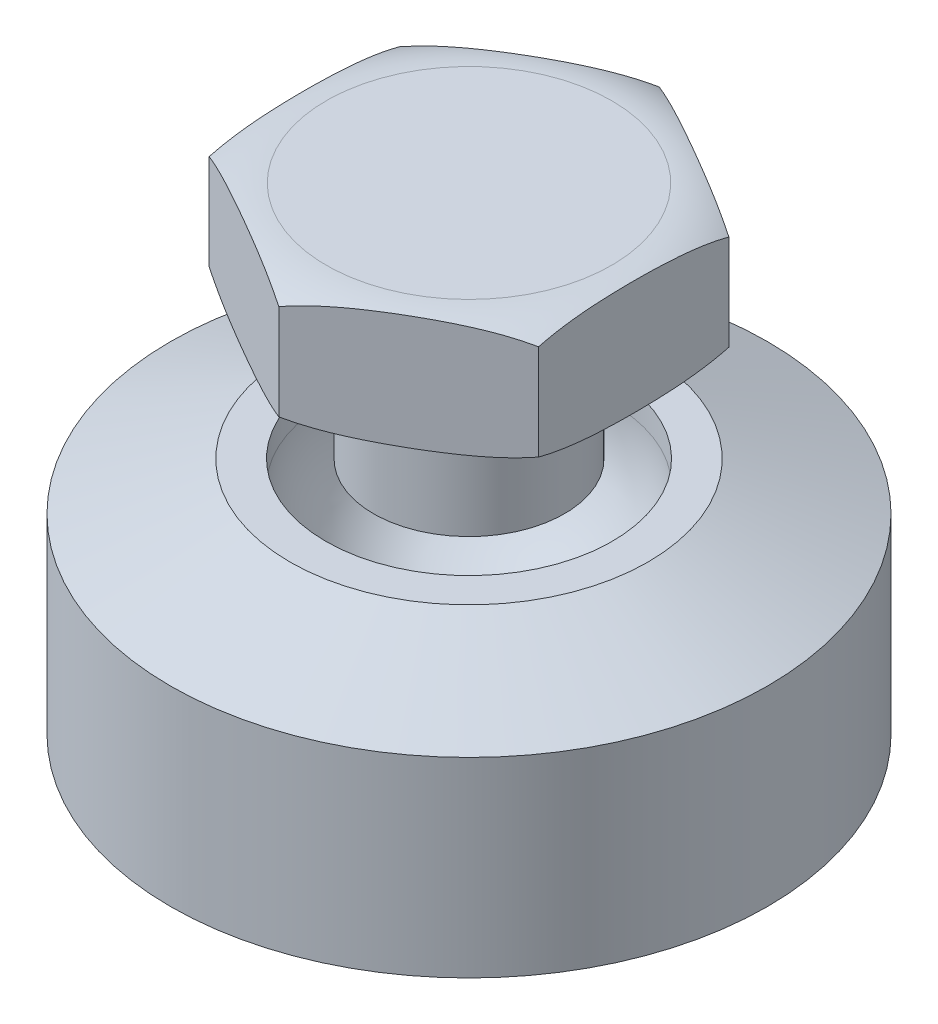
SolidWorks part; units mm, degrees
ref_plane "Front Plane" through (0, 0, 0) normal (0, 0, 1) x (1, 0, 0)
ref_plane "Top Plane" through (0, 0, 0) normal (0, 1, 0) x (1, 0, 0)
ref_plane "Right Plane" through (0, 0, 0) normal (1, 0, 0) x (0, 0, -1)
sketch "Sketch1" plane through (0, 0, 0) normal (0, 0, 1) x (1, 0, 0)
  line L0 (0, 280.7082) -> (0, 0) construction
  line L2 (12.5, 0) -> (12.5, 8)
  line L3 (12.5, 8) -> (7.5, 10)
  line L9 (7.5, 10) -> (6, 10)
  line L10 (6, 10) -> (6, 9)
  line L18 (3.75, 0) -> (3.75, 2.5)
  line L19 (3.75, 0) -> (12.5, 0)
  line L31 (3.75, 2.5) -> (0, 2.5)
  line L32 (0, 2.5) -> (0, 3.5228)
  arc A4 (0, 3.5228) -> (6, 9) centre (0.5, 9) ccw
  dimension "D14" = 5.5
  dimension "D1" = 12.5
  dimension "D2" = 8
  dimension "D3" = 15
  dimension "D4" = 10
  dimension "D12" = 12
  dimension "D13" = 1
  dimension "D15" = 7.5
  dimension "D16" = 2.5
revolve "Revolve1" add sketch "Sketch1" angle 360 about L0
sketch "Sketch7" plane through (0, 0, 0) normal (0, 0, 1) x (1, 0, 0)
  line L0 (4, 10) -> (4, 15)
  line L1 (4, 15) -> (0, 15)
  line L3 (0, 10) -> (4, 10)
  line L4 (0, 15) -> (0, 10)
  line L5 (7.5, 10) -> (-7.5, 10) construction
  line L6 (6, 10) -> (-6, 10) construction
  dimension "D1" = 5
  dimension "D2" = 4
revolve "Revolve2" add sketch "Sketch7" angle 360 about L4
sketch "Sketch8" plane through (0, 15, 0) normal (0, 1, 0) x (1, 0, 0)
  line L1 (0, 7.9674) -> (-6.9, 3.9837)
  line L2 (-6.9, 3.9837) -> (-6.9, -3.9837)
  line L3 (-6.9, -3.9837) -> (0, -7.9674)
  line L4 (0, -7.9674) -> (6.9, -3.9837)
  line L5 (6.9, -3.9837) -> (6.9, 3.9837)
  line L6 (6.9, 3.9837) -> (0, 7.9674)
  circle A0 centre (0, 0) radius 6.9 construction
  dimension "D1" = 13.8
extrude "Extrude3" add sketch "Sketch8" along normal blind 5
sketch "Sketch10" plane through (0, 0, 0) normal (1, 0, 0) x (0, 0, -1)
  line L0 (-7.9674, 20) -> (-7.9674, 19.5)
  line L1 (-7.9674, 20) -> (-7.9674, 15) construction
  line L2 (-7.9674, 20) -> (-5.9756, 20)
  line L3 (-7.9674, 20) -> (-3.9837, 20) construction
  line L4 (-7.9674, 17.5) -> (7.9674, 17.5) construction
  line L5 (7.9674, 20) -> (7.9674, 15) construction
  line L6 (-7.9674, 15) -> (-5.9756, 15)
  line L7 (-7.9674, 15) -> (-7.9674, 15.5)
  line L8 (0, 20) -> (0, 41.4972) construction
  line L9 (-3.9837, 20) -> (3.9837, 20) construction
  arc A0 (-5.9756, 20) -> (-7.9674, 19.5) centre (-5.9756, 15.7825) ccw
  arc A1 (-5.9756, 15) -> (-7.9674, 15.5) centre (-5.9756, 19.2175) cw
  dimension "D1" = 4
revolve "Cut-Revolve1" cut sketch "Sketch10" angle 360 about L8
